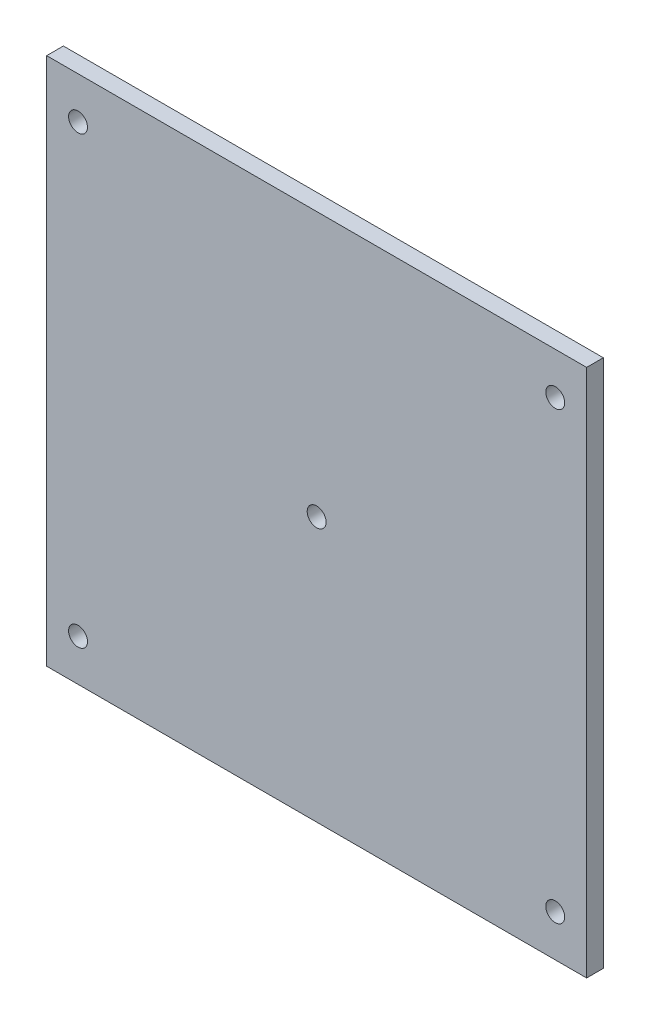
SolidWorks part; units mm, degrees
material "6061-T6 (SS)"
ref_plane "Front Plane" through (0, 0, 0) normal (0, 0, 1) x (1, 0, 0)
ref_plane "Top Plane" through (0, 0, 0) normal (0, 1, 0) x (1, 0, 0)
ref_plane "Right Plane" through (0, 0, 0) normal (1, 0, 0) x (0, 0, -1)
sketch "Body sketch" plane through (0, 0, 0) normal (0, 0, 1) x (1, 0, 0)
  line L1 (0, 0) -> (97, 0)
  line L2 (0, 0) -> (0, 95)
  line L3 (0, 95) -> (97, 95)
  line L4 (97, 0) -> (97, 95)
extrude "Body" add sketch "Body sketch" along normal blind 3
sketch "Holes sketch" plane through (0, 0, 0) normal (0, 0, 1) x (1, 0, 0)
  circle A0 centre (5.635, 7.495) radius 1.7
  circle A1 centre (91.365, 7.495) radius 1.7
  circle A2 centre (5.635, 87.505) radius 1.7
  circle A3 centre (91.365, 87.505) radius 1.7
  circle A4 centre (48.5, 47.5) radius 1.7
extrude "Holes" cut sketch "Holes sketch" against normal through all and the other way through all
